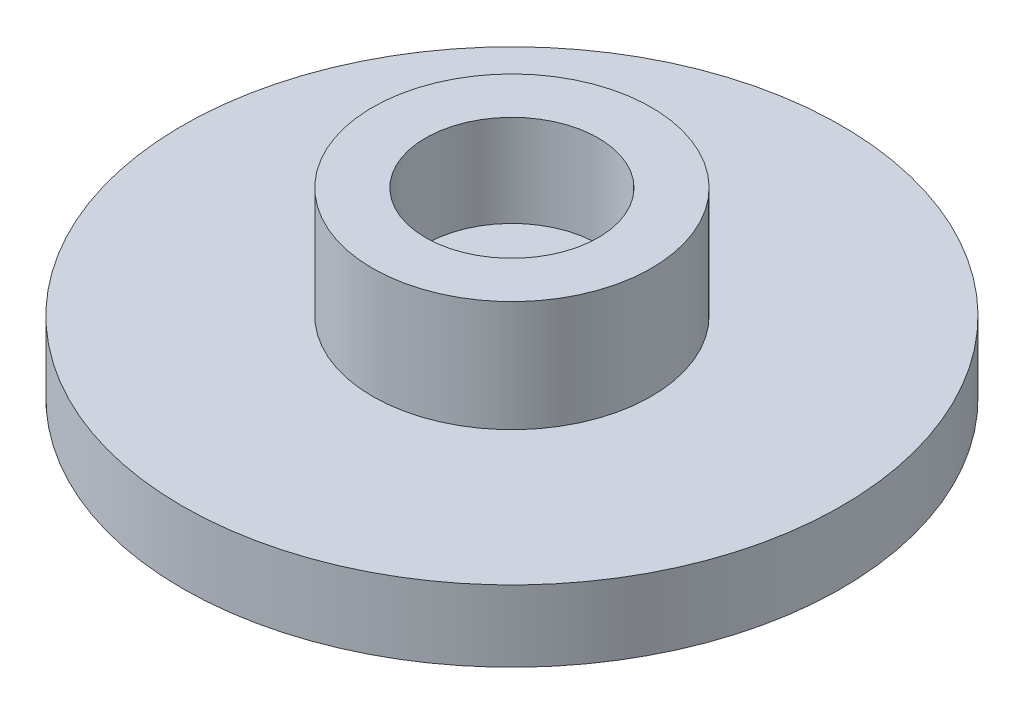
SolidWorks part; units mm, degrees
ref_plane "Alzado" through (0, 0, 0) normal (0, 0, 1) x (1, 0, 0)
ref_plane "Planta" through (0, 0, 0) normal (0, 1, 0) x (1, 0, 0)
ref_plane "Vista lateral" through (0, 0, 0) normal (1, 0, 0) x (0, 0, -1)
sketch "Croquis1" plane through (0, 0, 0) normal (0, 1, 0) x (1, 0, 0)
  circle A0 centre (0, 0) radius 10.4
  dimension "D1" = 20.8
extrude "Saliente-Extruir1" add sketch "Croquis1" along normal blind 2.25
sketch "Croquis2" plane through (0, 2.25, 0) normal (0, 1, 0) x (1, 0, 0)
  circle A0 centre (0, 0) radius 4.4
  dimension "D1" = 8.8
extrude "Saliente-Extruir2" add sketch "Croquis2" along normal blind 3.5
sketch "Croquis3" plane through (0, 5.75, 0) normal (0, 1, 0) x (1, 0, 0)
  circle A0 centre (0, 0) radius 2.725
  dimension "D1" = 5.45
extrude "Cortar-Extruir1" cut sketch "Croquis3" against normal blind 2.9
